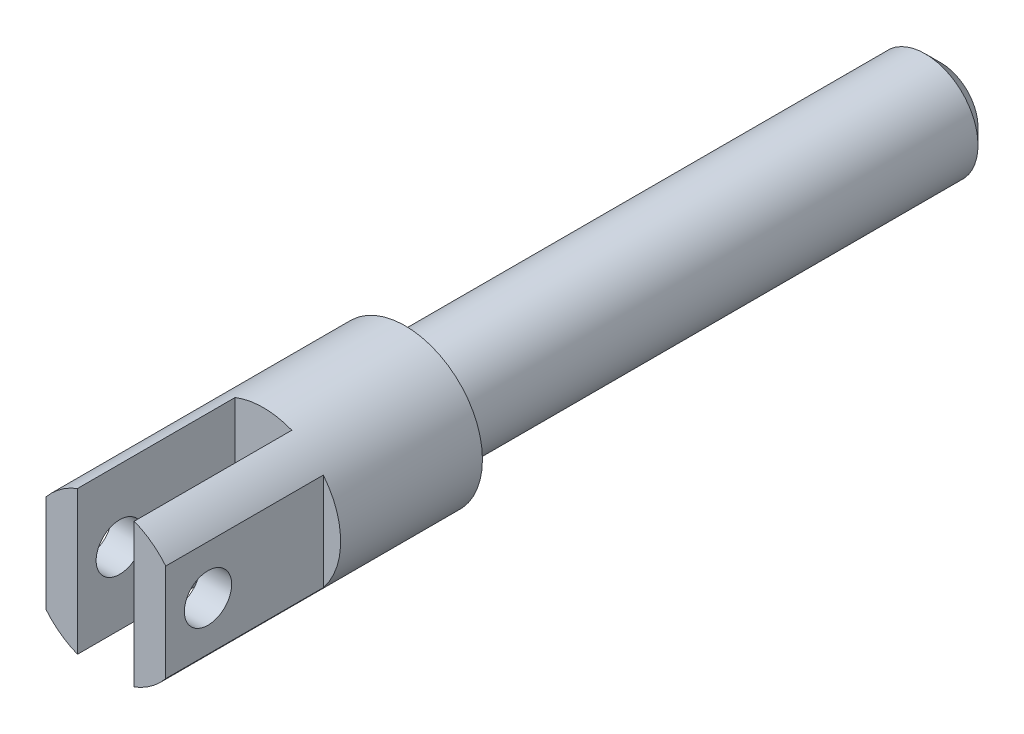
SolidWorks part; units mm, degrees
ref_plane "前视基准面" through (0, 0, 0) normal (0, 0, 1) x (1, 0, 0)
ref_plane "上视基准面" through (0, 0, 0) normal (0, 1, 0) x (1, 0, 0)
ref_plane "右视基准面" through (0, 0, 0) normal (1, 0, 0) x (0, 0, -1)
sketch "草图2" plane through (0, 0, 0) normal (0, 0, 1) x (1, 0, 0)
  circle A0 centre (0, 0) radius 4.9
  dimension "D1" = 9.8
extrude "凸台-拉伸1" add sketch "草图2" along normal blind 9
sketch "草图3" plane through (0, 0, 9) normal (0, 0, 1) x (1, 0, 0)
  line L0 (0, -4.9) -> (0, 4.9) construction
  line L1 (-1.8, -4.5574) -> (-1.8, 4.5574)
  line L2 (1.8, -4.5574) -> (1.8, 4.5574)
  line L3 (-3.8, -3.0935) -> (-3.8, 3.0935)
  line L4 (3.8, -3.0935) -> (3.8, 3.0935)
  line L6 (1.8, -4.9) -> (1.8, 4.9) construction
  line L7 (3.8, -4.9) -> (3.8, 4.9) construction
  line L8 (-3.8, -4.9) -> (-3.8, 4.9) construction
  line L9 (-1.8, -4.9) -> (-1.8, 4.9) construction
  circle A0 centre (0, 0) radius 4.9 construction
  arc A1 (-1.8, 4.5574) -> (-3.8, 3.0935) centre (0, 0) ccw
  arc A2 (1.8, -4.5574) -> (3.8, -3.0935) centre (0, 0) ccw
  arc A3 (3.8, 3.0935) -> (1.8, 4.5574) centre (0, 0) ccw
  arc A4 (-3.8, -3.0935) -> (-1.8, -4.5574) centre (0, 0) ccw
  dimension "D1" = 1.8
  dimension "D2" = 1.8
  dimension "D3" = 2
  dimension "D4" = 2
extrude "凸台-拉伸2" add sketch "草图3" along normal blind 10
sketch "草图4" plane through (-3.8, 0, 0) normal (-1, 0, 0) x (0, 0, 1)
  circle A0 centre (16.3188, 0) radius 1.5
  dimension "D1" = 3
extrude "切除-拉伸1" cut sketch "草图4" against normal through all
sketch "草图5" plane through (0, 0, 0) normal (0, 0, -1) x (-1, 0, 0)
  circle A0 centre (0, 0) radius 3.35
  dimension "D1" = 6.7
extrude "凸台-拉伸3" add sketch "草图5" along normal blind 34
chamfer "倒角1" distance 1 angle 45 1 edges at (-3.35, 0, -34)
